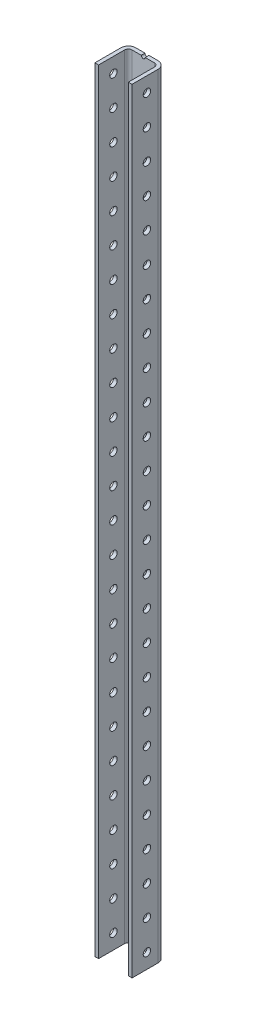
SolidWorks part; units mm, degrees
ref_plane "Front Plane" through (0, 0, 0) normal (0, 0, 1) x (1, 0, 0)
ref_plane "Top Plane" through (0, 0, 0) normal (0, 1, 0) x (1, 0, 0)
ref_plane "Right Plane" through (0, 0, 0) normal (1, 0, 0) x (0, 0, -1)
sketch "Sketch2" plane through (0, 0, 0) normal (0, 1, 0) x (1, 0, 0)
  line L0 (-12.7, 0) -> (12.7, 0) construction
  line L1 (-12.7, 0) -> (-12.7, 22.225)
  line L2 (-9.525, 25.4) -> (9.525, 25.4)
  line L3 (12.7, 22.225) -> (12.7, 0)
  line L4 (-15.875, 0) -> (-15.875, 22.225)
  line L5 (-9.525, 28.575) -> (9.525, 28.575)
  line L6 (15.875, 22.225) -> (15.875, 0)
  line L7 (-15.875, 0) -> (-12.7, 0)
  line L8 (12.7, 0) -> (15.875, 0)
  line L9 (-12.7, 25.4) -> (12.7, 25.4) construction
  line L10 (12.7, 25.4) -> (12.7, 0) construction
  line L11 (-12.7, 0) -> (-12.7, 25.4) construction
  line L12 (-15.875, 28.575) -> (15.875, 28.575) construction
  line L13 (15.875, 28.575) -> (15.875, 0) construction
  line L14 (-15.875, 0) -> (-15.875, 28.575) construction
  arc A0 (9.525, 25.4) -> (12.7, 22.225) centre (9.525, 22.225) cw
  arc A1 (-12.7, 22.225) -> (-9.525, 25.4) centre (-9.525, 22.225) cw
  arc A2 (9.525, 28.575) -> (15.875, 22.225) centre (9.525, 22.225) cw
  arc A3 (-15.875, 22.225) -> (-9.525, 28.575) centre (-9.525, 22.225) cw
  dimension "D4" = 3.175
  dimension "D5" = 6.35
  dimension "D1" = 25.4
  dimension "D2" = 25.4
  dimension "D3" = 3.175
extrude "Boss-Extrude1" add sketch "Sketch2" along normal mid plane 660.4
sketch "Sketch3" plane through (0, 0, -28.575) normal (0, 0, -1) x (-1, 0, 0)
  line L0 (0, 330.2) -> (0, -330.2) construction
  line L1 (-9.525, 330.2) -> (9.525, 330.2) construction
  line L2 (-9.525, -330.2) -> (9.525, -330.2) construction
  line L3 (-2.032, 444.5) -> (-2.032, -330.2) construction
  circle A0 centre (0, 330.2) radius 1.651
  circle A1 centre (-2.032, 222.25) radius 4.826
  circle A2 centre (-2.032, 196.85) radius 4.826
  circle A3 centre (-2.032, -6.35) radius 4.826
  circle A4 centre (-2.032, -57.15) radius 4.826
  circle A8 centre (2.032, -114.3) radius 4.826
  circle A9 centre (-2.032, -171.45) radius 4.826
  circle A10 centre (-2.032, -222.25) radius 4.826
  dimension "D1" = 3.302
  dimension "D3" = 9.652
  dimension "D14" = 9.652
  dimension "D11" = 9.652
  dimension "D2" = 2.032
  dimension "D4" = 107.95
  dimension "D5" = 25.4
  dimension "D6" = 57.15
  dimension "D7" = 50.8
  dimension "D8" = 114.3
  dimension "D9" = 50.8
  dimension "D10" = 107.95
  dimension "D15" = 2.032
extrude "Cut-Extrude1" cut sketch "Sketch3" against normal through all
sketch "Sketch4" plane through (15.875, 0, 0) normal (1, 0, 0) x (0, 0, -1)
  line L1 (0, 330.2) -> (22.225, 330.2) construction
  line L2 (0, 330.2) -> (0, -330.2) construction
  circle A0 centre (12.7, 317.5) radius 3.175
  dimension "D2" = 6.35
  dimension "D1" = 12.7
  dimension "D3" = 12.7
extrude "Cut-Extrude2" cut sketch "Sketch4" against normal through all
pattern_linear "LPattern1" count 26 spacing 25.4 along (0, -1, 0) of "Cut-Extrude2"
